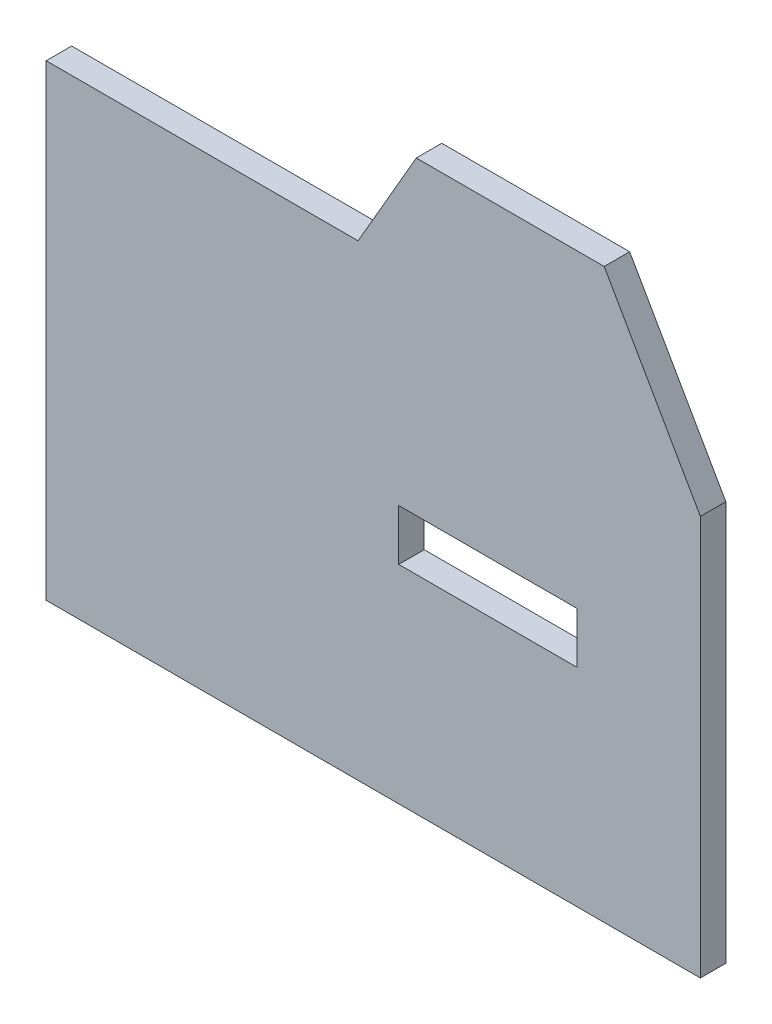
SolidWorks part; units mm, degrees
ref_plane "Front Plane" through (0, 0, 0) normal (0, 0, 1) x (1, 0, 0)
ref_plane "Top Plane" through (0, 0, 0) normal (0, 1, 0) x (1, 0, 0)
ref_plane "Right Plane" through (0, 0, 0) normal (1, 0, 0) x (0, 0, -1)
sketch "Sketch2" plane through (0, 0, 0) normal (0, 0, 1) x (1, 0, 0)
  line L0 (72.2895, 55) -> (72.4094, 55)
  line L1 (0, 0) -> (77, 0)
  line L2 (0, 0) -> (0, 55)
  line L11 (77, 0) -> (77, 47.0489)
  line L12 (0, 55) -> (36.7133, 55)
  line L15 (36.7133, 55) -> (43.5662, 66.8694)
  line L16 (43.5662, 66.8694) -> (65.6794, 66.8694)
  line L17 (65.6794, 66.8694) -> (77, 47.0489)
  dimension "D1" = 77
  dimension "D2" = 55
  dimension "D3" = 36.7133
  dimension "D4" = 47.0489
  dimension "D7" = 22.1133
extrude "Boss-Extrude1" add sketch "Sketch2" along normal blind 3
sketch "Sketch3" plane through (0, 0, 0) normal (0, 0, -1) x (-1, 0, 0)
  line L1 (-62.5, 24.41) -> (-41.5, 24.41)
  line L2 (-62.5, 24.41) -> (-62.5, 30.41)
  line L3 (-62.5, 30.41) -> (-41.5, 30.41)
  line L4 (-41.5, 24.41) -> (-41.5, 30.41)
  line L5 (0, 0) -> (-77, 0) construction
  line L6 (-77, 0) -> (-77, 47.0489) construction
  point P4 (-62.5, 27.41)
  point P5 (-52, 30.41)
  dimension "D1" = 21
  dimension "D2" = 6
  dimension "D3" = 24.41
  dimension "D4" = 14.5
extrude "Cut-Extrude1" cut sketch "Sketch3" against normal blind 10
